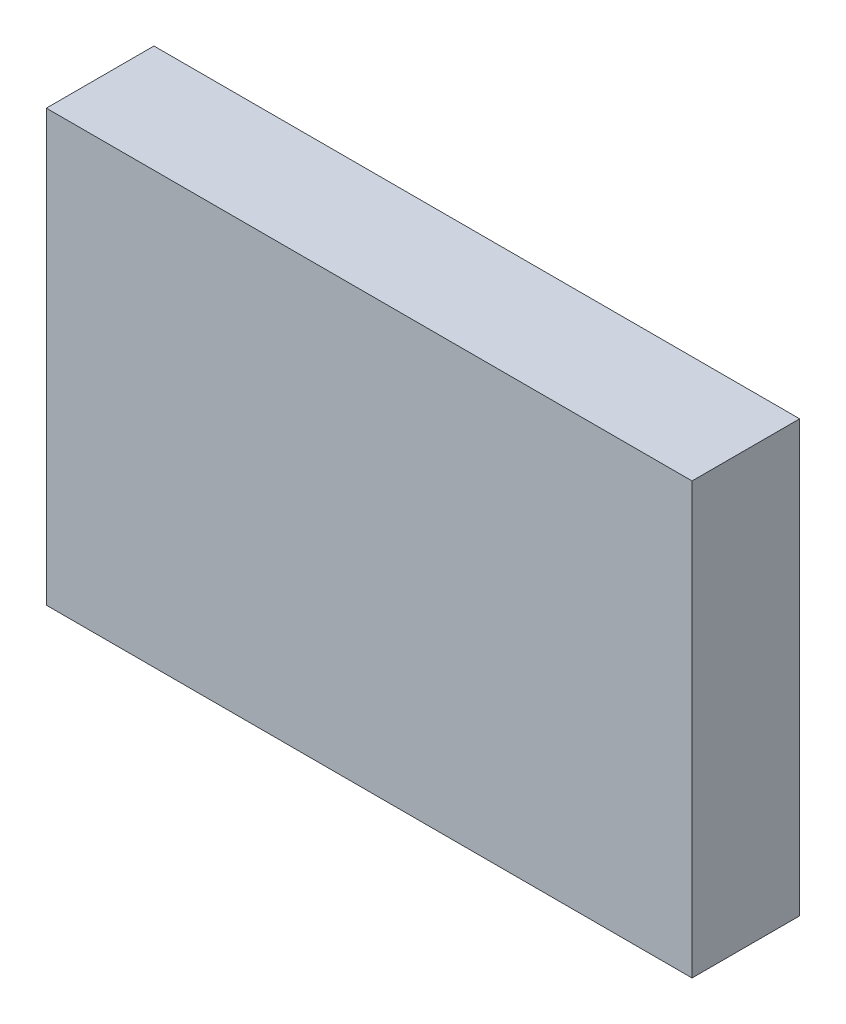
SolidWorks part; units mm, degrees
ref_plane "Přední rovina" through (0, 0, 0) normal (0, 0, 1) x (1, 0, 0)
ref_plane "Horní rovina" through (0, 0, 0) normal (0, 1, 0) x (1, 0, 0)
ref_plane "Pravá rovina" through (0, 0, 0) normal (1, 0, 0) x (0, 0, -1)
sketch "Sketch3" plane through (0, 0, 0) normal (0, 0, 1) x (1, 0, 0)
  line L1 (15, -10) -> (-15, -10)
  line L2 (15, -10) -> (15, 10)
  line L3 (15, 10) -> (-15, 10)
  line L4 (-15, -10) -> (-15, 10)
  line L5 (15, -10) -> (-15, 10) construction
  line L6 (15, 10) -> (-15, -10) construction
  point P0 (0, 0)
  dimension "D1" = 30
  dimension "D2" = 20
extrude "Boss-Extrude1" add sketch "Sketch3" along normal blind 5
equation "\"SH\" = 3mm"
equation "\"OH\" = 5mm"
equation "\"D1@Boss-Extrude1\"=\"OH\""
